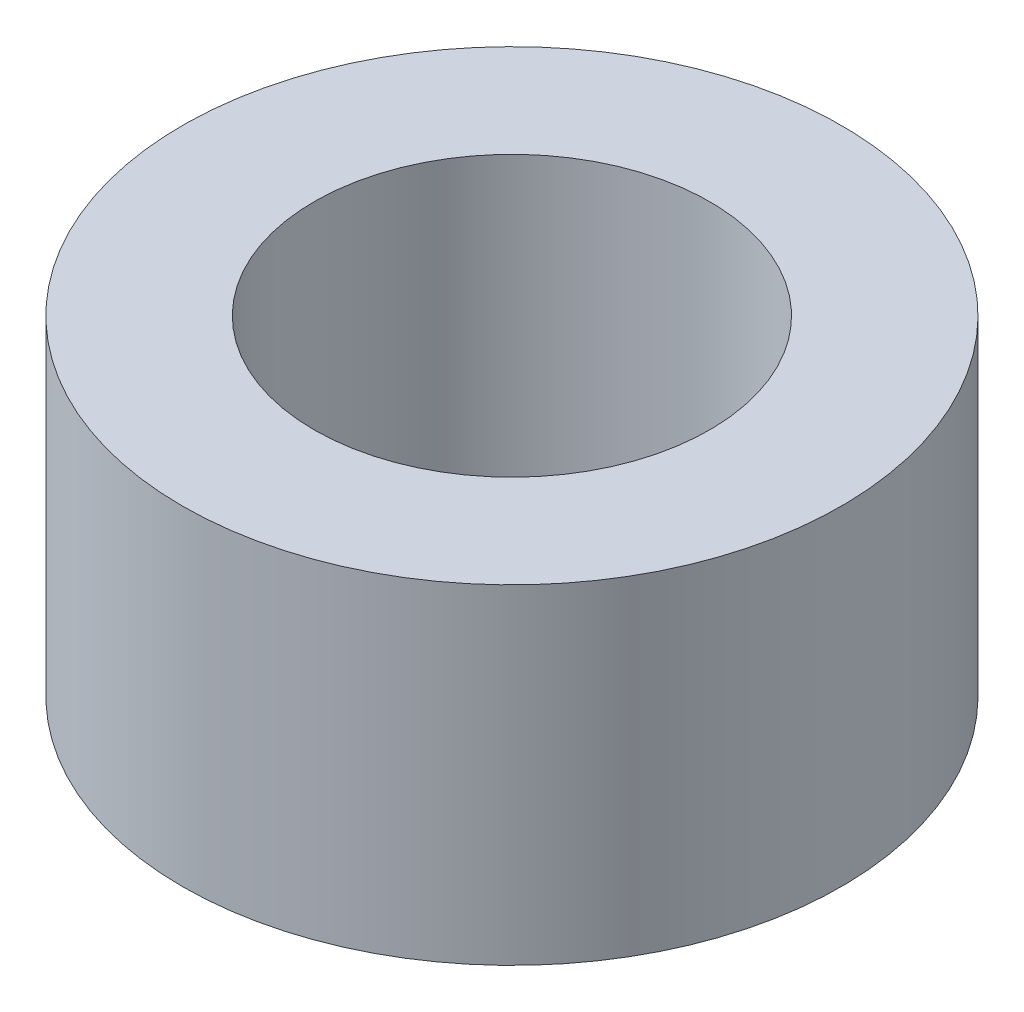
SolidWorks part; units mm, degrees
ref_plane "Front Plane" through (0, 0, 0) normal (0, 0, 1) x (1, 0, 0)
ref_plane "Top Plane" through (0, 0, 0) normal (0, 1, 0) x (1, 0, 0)
ref_plane "Right Plane" through (0, 0, 0) normal (1, 0, 0) x (0, 0, -1)
sketch "Sketch1" plane through (0, 0, 0) normal (0, 1, 0) x (1, 0, 0)
  circle A0 centre (0, 0) radius 5
  circle A1 centre (0, 0) radius 3
  dimension "D1" = 2
  dimension "D2" = 10
extrude "Boss-Extrude1" add sketch "Sketch1" along normal blind 5
